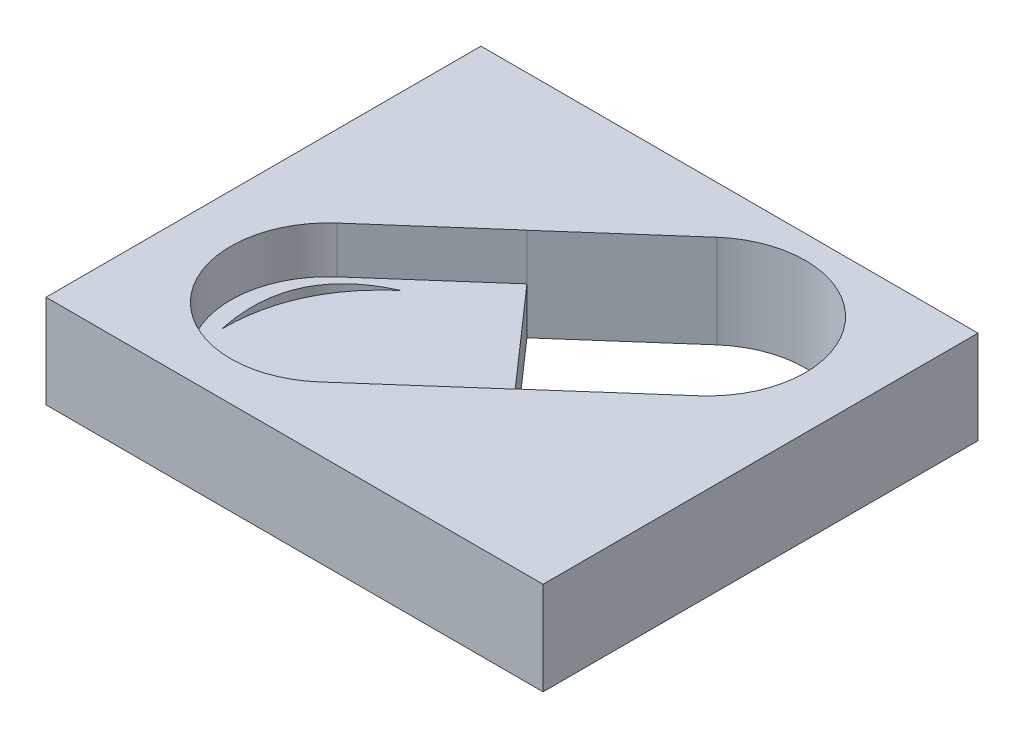
SolidWorks part; units mm, degrees
ref_plane "Front Plane" through (0, 0, 0) normal (0, 0, 1) x (1, 0, 0)
ref_plane "Top Plane" through (0, 0, 0) normal (0, 1, 0) x (1, 0, 0)
ref_plane "Right Plane" through (0, 0, 0) normal (1, 0, 0) x (0, 0, -1)
sketch "Sketch1" plane through (0, 0, 0) normal (0, 1, 0) x (1, 0, 0)
  line L1 (-42.8025, 22.3185) -> (-26.8025, 22.3185)
  line L2 (-42.8025, 22.3185) -> (-42.8025, 8.3185)
  line L3 (-42.8025, 8.3185) -> (-26.8025, 8.3185)
  line L4 (-26.8025, 22.3185) -> (-26.8025, 8.3185)
  dimension "D1" = 16
  dimension "D2" = 14
extrude "Boss-Extrude1" add sketch "Sketch1" along normal blind 3
sketch "Sketch2" plane through (0, 3, 0) normal (0, 1, 0) x (1, 0, 0)
  line L31 (-38.1144, 12.7151) -> (-31.6115, 18.4356) construction
  line L32 (-40.1829, 15.0665) -> (-33.68, 20.787)
  line L33 (-36.0459, 10.3637) -> (-29.543, 16.0842)
  line L34 (-36.9314, 17.9267) -> (-32.7944, 13.2239)
  arc A0 (-40.1829, 15.0665) -> (-36.0459, 10.3637) centre (-38.1144, 12.7151) ccw
  arc A1 (-29.543, 16.0842) -> (-33.68, 20.787) centre (-31.6115, 18.4356) ccw
  spline S0 degree 3 poles (-38.7651, 15.7293) (-40.696, 14.8514) (-40.9277, 13.3429) (-40.5891, 11.7603) knots 0 0 0 0 1 1 1 1
  spline S1 degree 2 poles (-40.5891, 11.7603) (-40.6011, 14.1567) (-38.7651, 15.7293) knots 0 0 0 1 1 1
  point P2 (-34.8629, 15.5753)
  point P13 (-38.7651, 15.7293)
  point P14 (-40.5891, 11.7603)
extrude "Cut-Extrude2" cut sketch "Sketch2" against normal blind 3
sketch "Sketch3" plane through (0, 3, 0) normal (0, 1, 0) x (1, 0, 0)
  line L0 (-31.6115, 18.4356) -> (-38.1144, 12.7151) construction
  line L1 (-32.7904, 13.2194) -> (-36.0419, 10.3591)
  line L2 (-36.9354, 17.9313) -> (-40.1869, 15.071)
  line L3 (-36.9354, 17.9313) -> (-32.7904, 13.2194)
  arc A1 (-40.1869, 15.071) -> (-36.0419, 10.3591) centre (-38.1144, 12.7151) ccw
  point P4 (-34.8629, 15.5753)
  point P12 (0, 0)
  point P13 (0, 0)
  point P14 (0, 0)
extrude "Cut-Extrude3" cut sketch "Sketch3" against normal blind 1.5
